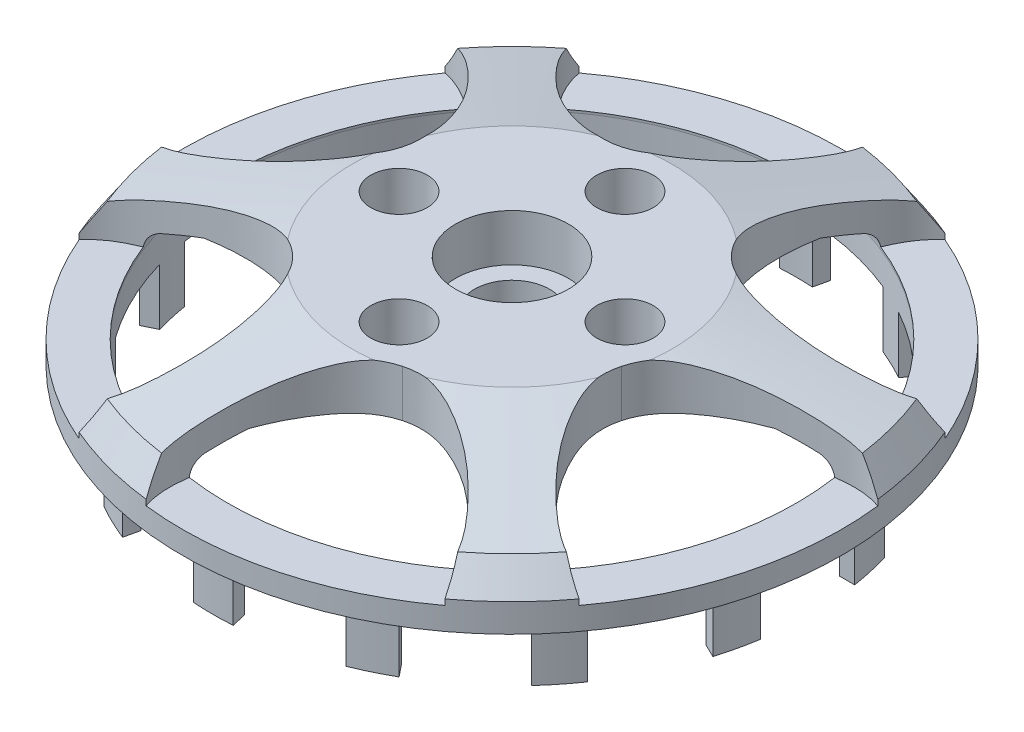
SolidWorks part; units mm, degrees
ref_plane "Спереди" through (0, 0, 0) normal (0, 0, 1) x (1, 0, 0)
ref_plane "Сверху" through (0, 0, 0) normal (0, 1, 0) x (1, 0, 0)
ref_plane "Справа" through (0, 0, 0) normal (1, 0, 0) x (0, 0, -1)
sketch "Эскиз2" plane through (0, 0, 0) normal (0, 0, 1) x (1, 0, 0)
  line L0 (0, 0) -> (0, 28.5055) construction
  line L1 (0, 0) -> (8.5, 0)
  line L2 (8.5, 0) -> (16.5, -2)
  line L3 (16.5, -2) -> (17.5, -3.5)
  line L4 (17.5, -3.5) -> (17.5, -5)
  line L5 (15.1, -8.5) -> (15.9, -8.5)
  line L6 (15.1, -8.5) -> (15.1, -3.15)
  line L7 (15.1, -3.15) -> (12.5, -2.5)
  line L8 (12.5, -2.5) -> (5.5, -2.5)
  line L9 (5.5, -2.5) -> (5.5, -4.5)
  line L10 (5.5, -4.5) -> (3, -5.5)
  line L11 (3, -5.5) -> (0, -5.5)
  line L12 (40.1518, 400.4586) -> (666.8184, 400.4586) construction
  line L15 (17.5, -5) -> (15.9, -5)
  line L16 (15.9, -8.5) -> (15.9, -5)
  line L17 (0, 0) -> (0, -5.5)
  point P8 (5.5, -3.5)
  point P14 (16.3233, 15.2486)
  point P19 (0, 0)
  point P20 (16.6737, 14.3215)
  point P21 (5.5, 13.1476)
  point P22 (5.5, 13.0163)
  point P23 (16.9475, 13.8907)
  point P24 (16.9445, 13.8595)
  point P25 (5.5, 12.9956)
  point P26 (12.5, 13.3646)
  point P27 (0, 15.5399)
  point P28 (16.5, 13.9777)
  point P29 (16.5, 9.1163)
  point P30 (0, 0.3431)
  dimension "D1" = 1.6
  dimension "D2" = 17.5
  dimension "D3" = 15.1
  dimension "D4" = 8.5
  dimension "D5" = 5.5
  dimension "D6" = 12.5
  dimension "D7" = 2.5
  dimension "D8" = 3
  dimension "D9" = 5.5
  dimension "D10" = 8.5
  dimension "D11" = 1.5
  dimension "D12" = 5
  dimension "D13" = 2
  dimension "D14" = 16.5
  dimension "D15" = 6.5
revolve "Повернуть1" add sketch "Эскиз2" angle 360 about L0
sketch "Эскиз3" plane through (0, 0, 0) normal (0, 1, 0) x (1, 0, 0)
  circle A0 centre (0, 0) radius 2
  circle A1 centre (0, 6) radius 1.5
  circle A2 centre (6, 0) radius 1.5
  circle A3 centre (0, -6) radius 1.5
  circle A4 centre (-6, 0) radius 1.5
  point P14 (0, 0)
  dimension "D1" = 4
  dimension "D2" = 3
  dimension "D3" = 6
  dimension "D4" = 4
extrude "Вырез-Вытянуть1" cut sketch "Эскиз3" against normal through all
sketch "Эскиз4" plane through (0, -8.5, 0) normal (0, -1, 0) x (1, 0, 0)
  line L0 (-12.2474, 2.5) -> (-12.2474, -2.5)
  line L1 (-20.0435, -2.5) -> (-12.2474, -2.5)
  line L2 (-20.0435, -2.5) -> (-20.0435, 2.5)
  line L3 (-20.0435, 2.5) -> (-12.2474, 2.5)
  line L4 (20.0435, -2.5) -> (20.0435, 2.5)
  line L5 (-20.0435, -2.5) -> (-12.2474, -1.5276) construction
  line L6 (-20.0435, 2.5) -> (-12.2474, 1.5276) construction
  line L7 (13.0614, 2.5) -> (13.0614, -2.5)
  line L8 (13.0614, 2.5) -> (20.0435, 2.5)
  line L9 (13.0614, -1.6291) -> (20.0435, -2.5) construction
  line L10 (13.0614, 1.6291) -> (20.0435, 2.5) construction
  line L11 (13.0614, -2.5) -> (20.0435, -2.5)
  circle A0 centre (0, 0) radius 12.5 construction
  point P0 (0, 0)
  dimension "D1" = 5
extrude "Вырез-Вытянуть2" cut sketch "Эскиз4" against normal blind 3
pattern_circular "Круговой массив1" count 14 over 360 about axis through (0, 0, 0) along (0, 1, 0) of "Вырез-Вытянуть2"
fillet "Скругление1" radius 1 1 edges at (0, -3.15, -15.1)
sketch "Эскиз5" plane through (0, 0, 0) normal (0, 1, 0) x (1, 0, 0)
  line L0 (-207.9523, 246.5567) -> (235.1679, 689.677) construction
  line L1 (0, 0) -> (14.9982, 14.9982) construction
  line L2 (6.9159, 16.0755) -> (13.0698, 17.3074)
  line L3 (13.0698, 17.3074) -> (17.7343, 13.3888)
  line L4 (17.7343, 13.3888) -> (16.0755, 6.9159)
  circle A0 centre (0, 0) radius 17.5 construction
  spline S0 degree 3 poles (6.9159, 16.0755) (6.0859, 15.3591) (4.9634, 12.8886) (4.3625, 9.1426) (5.0679, 6.5804) (5.8229, 5.8229) knots 0 0 0 0 0.287312 0.736997 1 1 1 1
  spline S1 degree 3 poles (16.0755, 6.9159) (15.3591, 6.0859) (12.8886, 4.9634) (9.1426, 4.3625) (6.5804, 5.0679) (5.8229, 5.8229) knots 0 0 0 0 0.287312 0.736997 1 1 1 1
  point P10 (5.823, 5.8228)
extrude "Вырез-Вытянуть5" cut sketch "Эскиз5" against normal blind 3.8
pattern_circular "Круговой массив2" count 6 over 360 about axis through (0, -8.5, 0) along (0, 1, 0) of "Вырез-Вытянуть5"
sketch "Эскиз6" plane through (0, 0, 0) normal (0, 1, 0) x (1, 0, 0)
  circle A0 centre (0, 0) radius 3
  dimension "D1" = 6
extrude "Вырез-Вытянуть6" cut sketch "Эскиз6" against normal blind 2.5
